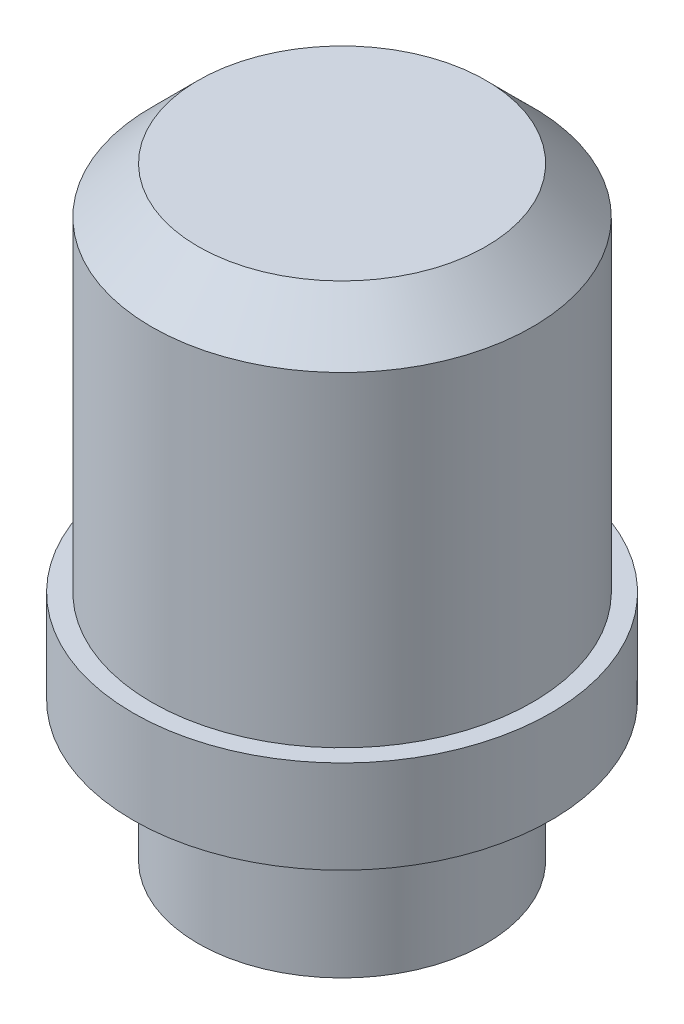
SolidWorks part; units mm, degrees
ref_plane "Front Plane" through (0, 0, 0) normal (0, 0, 1) x (1, 0, 0)
ref_plane "Top Plane" through (0, 0, 0) normal (0, 1, 0) x (1, 0, 0)
ref_plane "Right Plane" through (0, 0, 0) normal (1, 0, 0) x (0, 0, -1)
sketch "Sketch1" plane through (0, 0, 0) normal (0, 1, 0) x (1, 0, 0)
  circle A0 centre (0, 0) radius 3.1
  dimension "D1" = 6.2
extrude "Boss-Extrude1" add sketch "Sketch1" along normal blind 5
ref_plane "Plane4" through (0, 3, 0) normal (0, 1, 0) x (1, 0, 0)
sketch "Sketch2" plane through (0, 3, 0) normal (0, 1, 0) x (1, 0, 0)
  circle A1 centre (0, 0) radius 4.5
  dimension "D1" = 9
extrude "Boss-Extrude2" add sketch "Sketch2" along normal blind 2
sketch "Sketch3" plane through (0, 5, 0) normal (0, 1, 0) x (1, 0, 0)
  circle A0 centre (0, 0) radius 4.1
  dimension "D1" = 8.2
extrude "Boss-Extrude3" add sketch "Sketch3" along normal blind 8
chamfer "Chamfer1" distance 1 angle 45 1 edges at (0, 13, 4.1)
